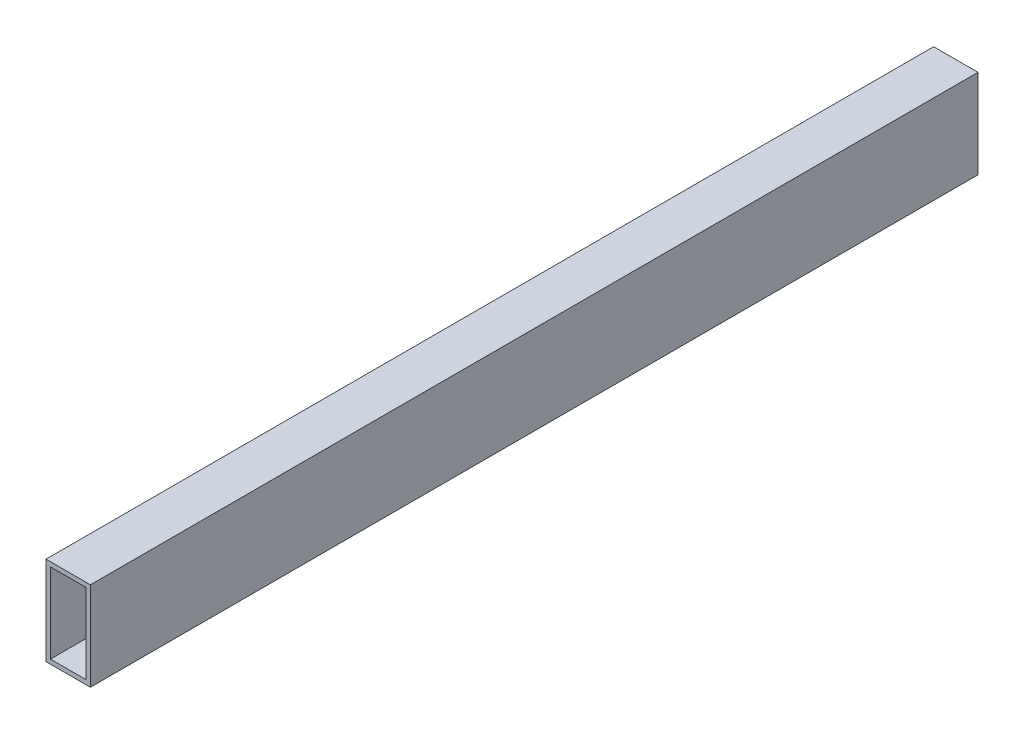
SolidWorks part; units mm, degrees
ref_plane "Front Plane" through (0, 0, 0) normal (0, 0, 1) x (1, 0, 0)
ref_plane "Top Plane" through (0, 0, 0) normal (0, 1, 0) x (1, 0, 0)
ref_plane "Right Plane" through (0, 0, 0) normal (1, 0, 0) x (0, 0, -1)
sketch "Sketch1" plane through (0, 0, 0) normal (0, 0, 1) x (1, 0, 0)
  line L1 (-12.5, 25) -> (12.5, 25)
  line L2 (-12.5, 25) -> (-12.5, -25)
  line L3 (-12.5, -25) -> (12.5, -25)
  line L4 (12.5, 25) -> (12.5, -25)
  line L5 (-12.5, 25) -> (12.5, -25) construction
  line L6 (-12.5, -25) -> (12.5, 25) construction
  line L7 (-10, 22.5) -> (10, 22.5)
  line L8 (-10, 22.5) -> (-10, -22.5)
  line L9 (-10, -22.5) -> (10, -22.5)
  line L10 (10, 22.5) -> (10, -22.5)
  line L11 (-10, 22.5) -> (10, -22.5) construction
  line L12 (-10, -22.5) -> (10, 22.5) construction
  point P0 (0, 0)
  point P6 (0, 0)
  point P11 (9.6091, -22.2364)
  dimension "D1" = 50
  dimension "D2" = 25
  dimension "D3" = 2.5
  dimension "D4" = 2.5
extrude "Boss-Extrude1" add sketch "Sketch1" along normal blind 500
